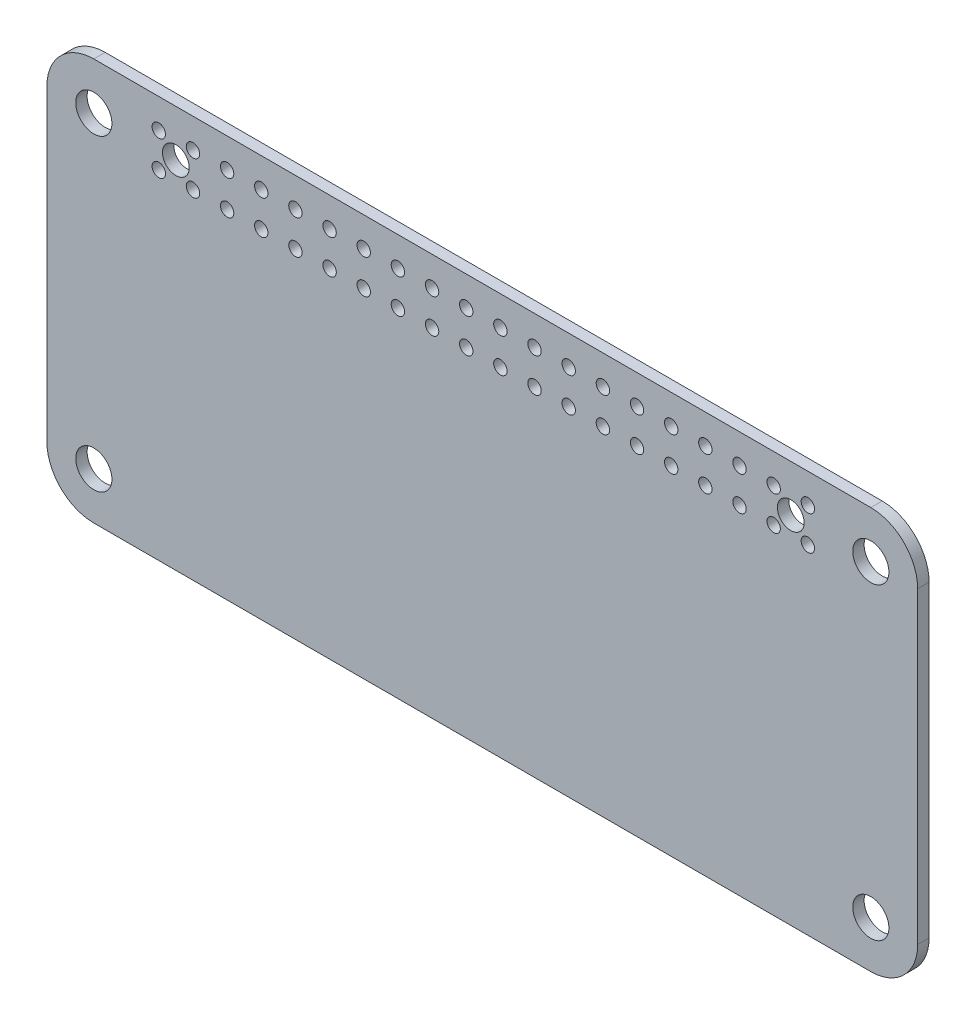
SolidWorks part; units mm, degrees
ref_plane "前视基准面" through (0, 0, 0) normal (0, 0, 1) x (1, 0, 0)
ref_plane "上视基准面" through (0, 0, 0) normal (0, 1, 0) x (1, 0, 0)
ref_plane "右视基准面" through (0, 0, 0) normal (1, 0, 0) x (0, 0, -1)
sketch "草图1" plane through (0, 0, 0) normal (0, 0, 1) x (1, 0, 0)
  line L1 (-3.5, 3.5) -> (61.5, 3.5)
  line L2 (-3.5, 3.5) -> (-3.5, -26.5)
  line L3 (-3.5, -26.5) -> (61.5, -26.5)
  line L4 (61.5, 3.5) -> (61.5, -26.5)
  point P4 (-3.5, 3.5022)
  point P5 (0, 0)
  point P9 (-2.1855, 3.5022)
  dimension "D1" = 3.5
  dimension "D2" = 3.5
  dimension "D3" = 30
  dimension "D4" = 65
extrude "凸台-拉伸1" add sketch "草图1" along normal blind 0.85
fillet "圆角1" radius 3.5 4 edges at (61.5, 3.5, 0.425) (61.5, -26.5, 0.425) (-3.5, -26.5, 0.425) (-3.5, 3.5, 0.425)
hole_wizard "M2 间隙孔1" positions "草图2" profile "草图3" hole size "M2" standard "GB" end condition through all
sketch "草图2" plane through (0, 0, 0.85) normal (0, 0, 1) x (1, 0, 0)
  arc A0 (-3.5, -23) -> (0, -26.5) centre (0, -23) ccw construction
  arc A1 (0, 3.5) -> (-3.5, 0) centre (0, 0) ccw construction
  arc A2 (61.5, 0) -> (58, 3.5) centre (58, 0) ccw construction
  arc A3 (58, -26.5) -> (61.5, -23) centre (58, -23) ccw construction
  point P0 (0, 0)
  point P2 (58, 0)
  point P4 (58, -23)
  point P6 (0, -23)
  point P12 (0, 0)
  point P13 (0, -3.2018)
  point P20 (0, 0)
sketch "草图3" plane through (0, 0, 0.85) normal (1, 0, 0) x (0, -1, 0)
  line L0 (0, 0) -> (0, 0.85)
  line L1 (0, 0.85) -> (1.35, 0.85)
  line L2 (1.35, 0.85) -> (1.35, 0)
  line L5 (1.35, 0) -> (0, 0)
  line L11 (0, -6.35) -> (0, 107.95) construction
  dimension "通孔孔直径" = 2.7
  dimension "通孔孔深度" = 0.85
sketch "草图6" plane through (0, 0, 0) normal (0, 0, -1) x (-1, 0, 0)
  line L0 (-58, 3.5) -> (0, 3.5) construction
  circle A0 centre (-4.85, 1.3) radius 0.5
  circle A1 centre (-4.85, -1.25) radius 0.5
  circle A2 centre (-7.4, -1.25) radius 0.5
  circle A3 centre (-7.4, 1.3) radius 0.5
  circle A4 centre (-9.95, 1.3) radius 0.5
  circle A5 centre (-9.95, -1.25) radius 0.5
  circle A6 centre (-12.5, -1.25) radius 0.5
  circle A7 centre (-12.5, 1.3) radius 0.5
  circle A8 centre (-15.05, 1.3) radius 0.5
  circle A9 centre (-15.05, -1.25) radius 0.5
  circle A10 centre (-17.6, -1.25) radius 0.5
  circle A11 centre (-17.6, 1.3) radius 0.5
  circle A12 centre (-20.15, 1.3) radius 0.5
  circle A13 centre (-20.15, -1.25) radius 0.5
  circle A14 centre (-22.7, -1.25) radius 0.5
  circle A15 centre (-22.7, 1.3) radius 0.5
  circle A16 centre (-25.25, 1.3) radius 0.5
  circle A17 centre (-25.25, -1.25) radius 0.5
  circle A18 centre (-27.8, -1.25) radius 0.5
  circle A19 centre (-27.8, 1.3) radius 0.5
  circle A20 centre (-30.35, 1.3) radius 0.5
  circle A21 centre (-30.35, -1.25) radius 0.5
  circle A22 centre (-32.9, -1.25) radius 0.5
  circle A23 centre (-32.9, 1.3) radius 0.5
  circle A24 centre (-35.45, 1.3) radius 0.5
  circle A25 centre (-35.45, -1.25) radius 0.5
  circle A26 centre (-38, -1.25) radius 0.5
  circle A27 centre (-38, 1.3) radius 0.5
  circle A28 centre (-40.55, 1.3) radius 0.5
  circle A29 centre (-40.55, -1.25) radius 0.5
  circle A30 centre (-43.1, -1.25) radius 0.5
  circle A31 centre (-43.1, 1.3) radius 0.5
  circle A32 centre (-45.65, 1.3) radius 0.5
  circle A33 centre (-45.65, -1.25) radius 0.5
  circle A34 centre (-48.2, -1.25) radius 0.5
  circle A35 centre (-48.2, 1.3) radius 0.5
  circle A36 centre (-50.75, 1.3) radius 0.5
  circle A37 centre (-50.75, -1.25) radius 0.5
  circle A38 centre (-53.3, -1.25) radius 0.5
  circle A39 centre (-53.3, 1.3) radius 0.5
  circle A40 centre (-6.125, 0.025) radius 1
  circle A41 centre (-52.025, 0.025) radius 1
  dimension "D1" = 2.2
  dimension "D2" = 1
  dimension "D4" = 2.55
  dimension "D5" = 2.55
  dimension "D8" = 2
  dimension "D10" = 1.275
  dimension "D11" = 2
  dimension "D12" = 1.275
  dimension "D13" = 1.275
  dimension "D3" = 4.85
  dimension "D7" = 2.55
  dimension "D9" = 1.275
  dimension "D6" = 10
extrude "切除-拉伸1" cut sketch "草图6" against normal through all
